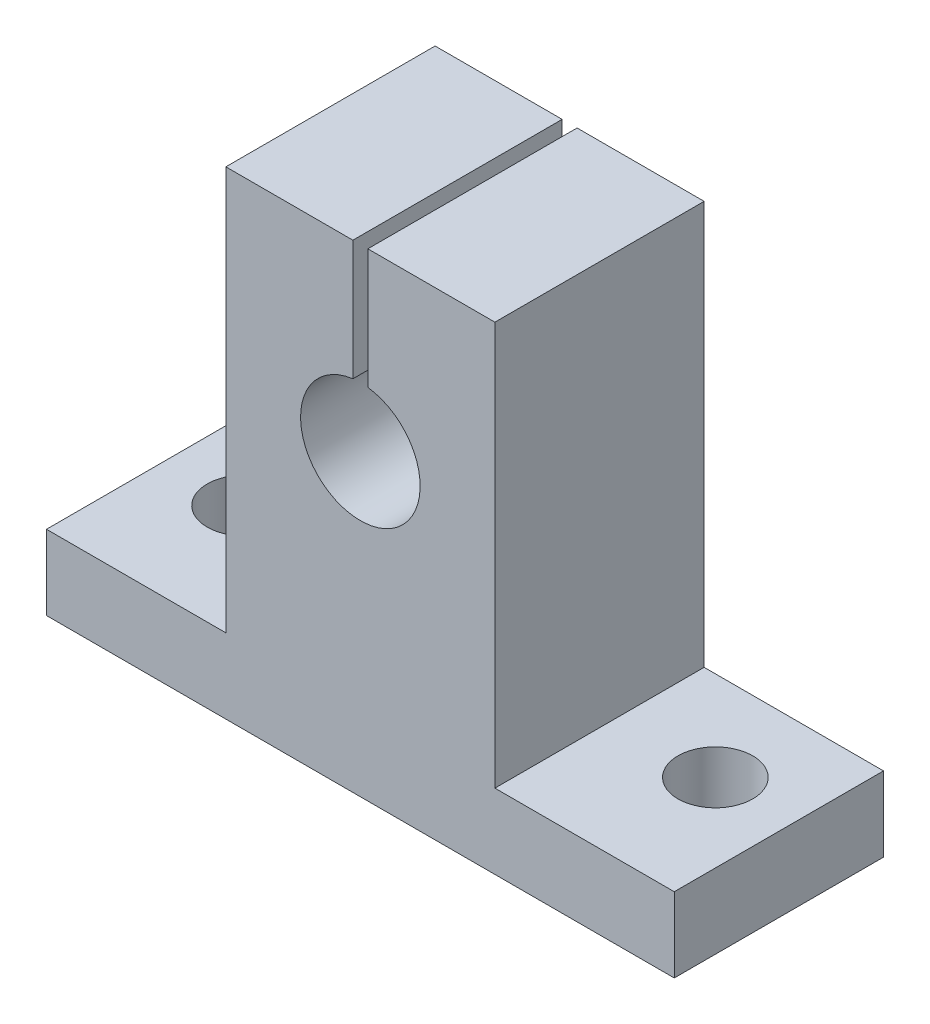
SolidWorks part; units mm, degrees
material "Alliage 1060"
ref_plane "Plan de face" through (0, 0, 0) normal (0, 0, 1) x (1, 0, 0)
ref_plane "Plan de dessus" through (0, 0, 0) normal (0, 1, 0) x (1, 0, 0)
ref_plane "Plan de droite" through (0, 0, 0) normal (1, 0, 0) x (0, 0, -1)
sketch "Esquisse1" plane through (0, 0, 0) normal (0, 1, 0) x (1, 0, 0)
  line L1 (21, 7) -> (-21, 7)
  line L2 (21, 7) -> (21, -7)
  line L3 (21, -7) -> (-21, -7)
  line L4 (-21, 7) -> (-21, -7)
  line L5 (21, 7) -> (-21, -7) construction
  line L6 (21, -7) -> (-21, 7) construction
  point P0 (0, 0)
  dimension "D1" = 14
  dimension "D2" = 42
extrude "Boss.-Extru.1" add sketch "Esquisse1" along normal blind 32
sketch "Esquisse2" plane through (0, 0, 7) normal (0, 0, 1) x (1, 0, 0)
  line L1 (-21, 32) -> (-9, 32)
  line L2 (-21, 32) -> (-21, 5)
  line L3 (-21, 5) -> (-9, 5)
  line L4 (-9, 32) -> (-9, 5)
  line L5 (21, 32) -> (9, 32)
  line L6 (21, 32) -> (21, 5)
  line L7 (21, 5) -> (9, 5)
  line L8 (9, 32) -> (9, 5)
  dimension "D1" = 27
  dimension "D2" = 12
extrude "Enlèv. mat.-Extru.1" cut sketch "Esquisse2" against normal through all
sketch "Esquisse3" plane through (0, 0, 7) normal (0, 0, 1) x (1, 0, 0)
  circle A0 centre (0, 20) radius 4
  dimension "D1" = 8
  dimension "D2" = 20
extrude "Enlèv. mat.-Extru.2" cut sketch "Esquisse3" against normal through all
sketch "Esquisse4" plane through (0, 0, 7) normal (0, 0, 1) x (1, 0, 0)
  line L0 (-9, 32) -> (9, 32) construction
  line L1 (-0.5, 18.0387) -> (0.5, 18.0387)
  line L2 (-0.5, 18.0387) -> (-0.5, 32)
  line L3 (-0.5, 32) -> (0.5, 32)
  line L4 (0.5, 18.0387) -> (0.5, 32)
  point P4 (0, 18.0387)
  dimension "D1" = 1
extrude "Enlèv. mat.-Extru.3" cut sketch "Esquisse4" against normal through all
sketch "Esquisse5" plane through (0, 5, 0) normal (0, 1, 0) x (1, 0, 0)
  line L0 (-15.75, 1) -> (15.75, 1) construction
  line L2 (-21, 7) -> (-9, 7) construction
  circle A2 centre (-15.75, 1) radius 2.5
  circle A4 centre (15.75, 1) radius 2.5
  point P7 (0, 1)
  dimension "D1" = 5
  dimension "D2" = 6
  dimension "D3" = 31.5
extrude "Enlèv. mat.-Extru.4" cut sketch "Esquisse5" against normal through all
